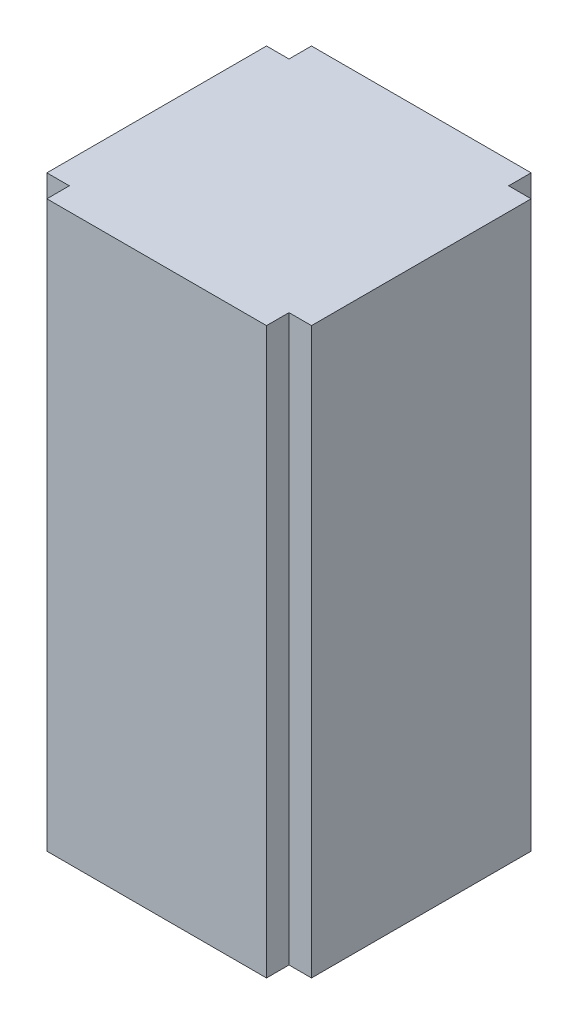
SolidWorks part; units mm, degrees
material "Custom Plastic"
ref_plane "Front Plane" through (0, 0, 0) normal (0, 0, 1) x (1, 0, 0)
ref_plane "Top Plane" through (0, 0, 0) normal (0, 1, 0) x (1, 0, 0)
ref_plane "Right Plane" through (0, 0, 0) normal (1, 0, 0) x (0, 0, -1)
sketch "Sketch1" plane through (0, 0, 0) normal (0, 1, 0) x (1, 0, 0)
  line L5 (27.5908, -51.6959) -> (27.5908, -43.1959)
  line L6 (36.0908, -43.1959) -> (36.0908, 39.8041)
  line L10 (36.0908, 39.8041) -> (27.5908, 39.8041)
  line L11 (-55.4092, 39.8041) -> (-55.4092, 48.3041)
  line L12 (27.5908, 39.8041) -> (27.5908, 48.3041)
  line L13 (-55.4092, 48.3041) -> (27.5908, 48.3041)
  line L15 (-55.4092, 39.8041) -> (-63.9092, 39.8041)
  line L16 (-55.4092, -43.1959) -> (-63.9092, -43.1959)
  line L17 (-63.9092, 39.8041) -> (-63.9092, -43.1959)
  line L19 (-55.4092, -43.1959) -> (-55.4092, -51.6959)
  line L21 (-55.4092, -51.6959) -> (27.5908, -51.6959)
  line L22 (36.0908, -43.1959) -> (27.5908, -43.1959)
  point P0 (0, 0)
  dimension "D1" = 100
  dimension "D2" = 100
  dimension "D3" = 8.5
extrude "Boss-Extrude1" add sketch "Sketch1" along normal mid plane 213.5 contours L17 L16 L19 L21 L5 L22 L6 L10 L12 L13 L11 L15
